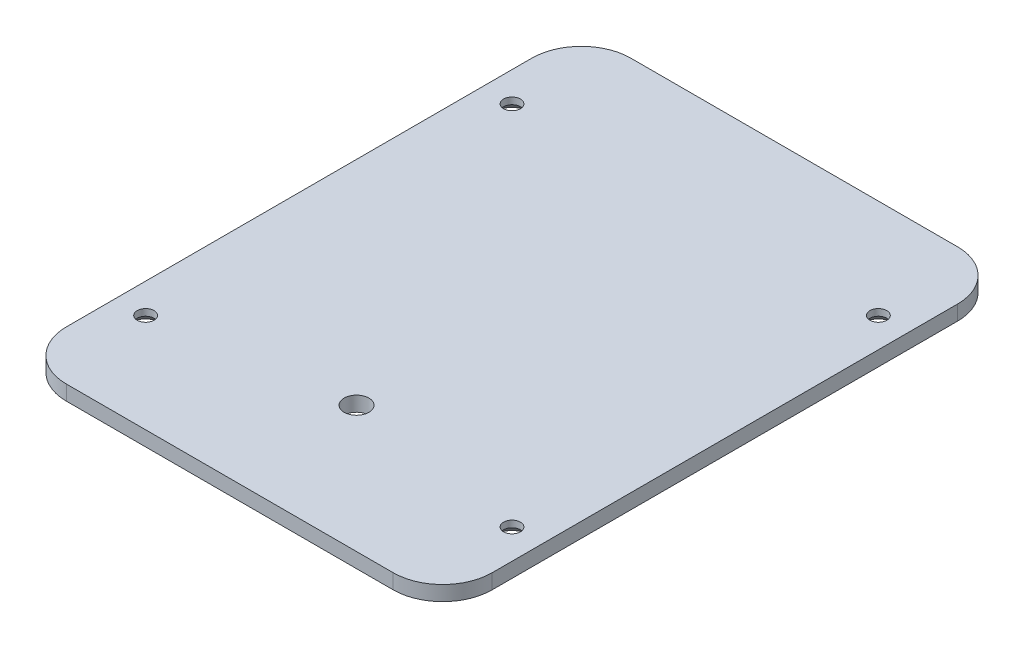
SolidWorks part; units mm, degrees
ref_plane "Front Plane" through (0, 0, 0) normal (0, 0, 1) x (1, 0, 0)
ref_plane "Top Plane" through (0, 0, 0) normal (0, 1, 0) x (1, 0, 0)
ref_plane "Right Plane" through (0, 0, 0) normal (1, 0, 0) x (0, 0, -1)
sketch "Sketch1" plane through (0, 0, 0) normal (0, 1, 0) x (1, 0, 0)
  line L0 (33, -57) -> (-33, -57) construction
  line L1 (43, 47) -> (43, -47) construction
  line L2 (-33, 57) -> (33, 57) construction
  line L3 (-43, -47) -> (-43, 47) construction
  line L4 (33, -57) -> (-33, -57)
  line L5 (43, 47) -> (43, -47)
  line L6 (-33, 57) -> (33, 57)
  line L7 (-43, -47) -> (-43, 47)
  arc A0 (-43, -47) -> (-33, -57) centre (-33, -47) ccw construction
  arc A1 (33, -57) -> (43, -47) centre (33, -47) ccw construction
  arc A2 (43, 47) -> (33, 57) centre (33, 47) ccw construction
  arc A3 (-33, 57) -> (-43, 47) centre (-33, 47) ccw construction
  arc A4 (-43, -47) -> (-33, -57) centre (-33, -47) ccw
  arc A5 (33, -57) -> (43, -47) centre (33, -47) ccw
  arc A6 (43, 47) -> (33, 57) centre (33, 47) ccw
  arc A7 (-33, 57) -> (-43, 47) centre (-33, 47) ccw
extrude "Boss-Extrude1" add sketch "Sketch1" along normal blind 3
sketch "Sketch3" plane through (0, 0, 0) normal (0, -1, 0) x (1, 0, 0)
  circle A0 centre (0, 31.4) radius 2.5 construction
  circle A1 centre (0, 31.4) radius 2.5
extrude "Cut-Extrude1" cut sketch "Sketch3" against normal blind 3
hole_wizard "CSK for M3 Hex Socket Countersunk Cap Screw1" positions "Sketch4" profile "Sketch5" countersink size "M3" standard "ISO"
sketch "Sketch4" plane through (0, 0, 0) normal (0, -1, 0) x (-1, 0, 0)
  line L1 (31, 47) -> (31, -47) construction
  line L3 (43, 0) -> (31, 0) construction
  line L6 (0, 0) -> (0, 47) construction
  line L8 (37, 37) -> (37, 0) construction
  line L10 (37, 0) -> (37, -37) construction
  point P0 (37, 37)
  point P2 (37, -37)
  point P4 (-37, 37)
  point P6 (-37, -37)
sketch "Sketch5" plane through (-37, 0, -37) normal (1, 0, 0) x (0, 0, -1)
  line L0 (0, 0) -> (0, 21.0215)
  line L1 (0, 21.0215) -> (1.7, 20)
  line L2 (1.7, 20) -> (1.7, 1.66)
  line L3 (1.7, 1.66) -> (3.36, 0)
  line L4 (3.36, 0) -> (0, 0)
  line L5 (-1.7, 1.66) -> (-3.36, 0) construction
  line L6 (0, 21.0215) -> (-1.7, 20) construction
  line L7 (0, -6.35) -> (0, 107.95) construction
  dimension "Hole Dia." = 3.4
  dimension "Hole Depth" = 20
  dimension "Near C'Sink Dia." = 6.72
  dimension "Near C'Sink Angle" = 90
  dimension "Drill Angle" = 118
